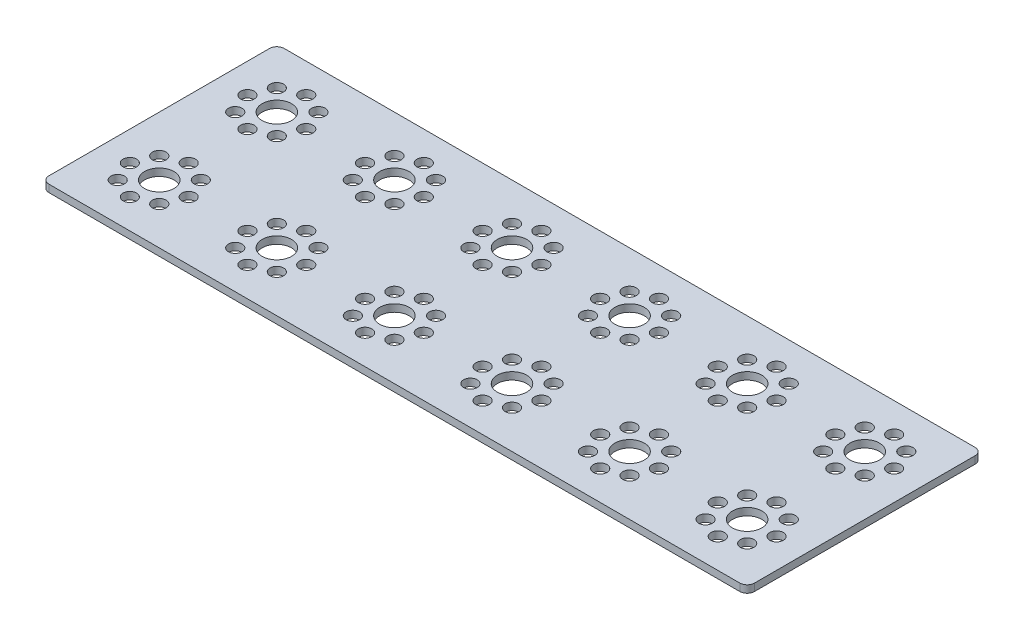
SolidWorks part; units mm, degrees
material "5052 Alloy"
ref_plane "Front Plane" through (0, 0, 0) normal (0, 0, 1) x (1, 0, 0)
ref_plane "Top Plane" through (0, 0, 0) normal (0, 1, 0) x (1, 0, 0)
ref_plane "Right Plane" through (0, 0, 0) normal (1, 0, 0) x (0, 0, -1)
sketch "Sketch1" plane through (0, 0, 0) normal (0, 1, 0) x (1, 0, 0)
  line L1 (0, 0) -> (192, 0)
  line L2 (0, 0) -> (0, 64)
  line L3 (0, 64) -> (192, 64)
  line L4 (192, 0) -> (192, 64)
  dimension "D1" = 192
  dimension "D2" = 64
extrude "Extrude1" add sketch "Sketch1" along normal blind 2
sketch "Sketch2" plane through (0, 2, 0) normal (0, 1, 0) x (1, 0, 0)
  line L0 (192, 64) -> (0, 64) construction
  line L1 (96, 64) -> (96, 84.1401) construction
  line L2 (96, 64) -> (96, -20.9972) construction
  line L3 (96, -20.9972) -> (96, 0) construction
  line L4 (0, 0) -> (192, 0) construction
  circle B0 centre (80, 48) radius 4
  circle B1 centre (80, 40) radius 1.85
  circle B2 centre (80, 56) radius 1.85
  circle B3 centre (72, 48) radius 1.85
  circle B4 centre (88, 48) radius 1.85
  circle B5 centre (85.66, 53.66) radius 1.85
  circle B6 centre (74.34, 53.66) radius 1.85
  circle B7 centre (85.66, 42.34) radius 1.85
  circle B8 centre (74.34, 42.34) radius 1.85
  circle B9 centre (48, 48) radius 4
  circle B10 centre (48, 40) radius 1.85
  circle B11 centre (48, 56) radius 1.85
  circle B12 centre (40, 48) radius 1.85
  circle B13 centre (56, 48) radius 1.85
  circle B14 centre (53.66, 53.66) radius 1.85
  circle B15 centre (42.34, 53.66) radius 1.85
  circle B16 centre (53.66, 42.34) radius 1.85
  circle B17 centre (42.34, 42.34) radius 1.85
  circle B18 centre (16, 48) radius 4
  circle B19 centre (16, 40) radius 1.85
  circle B20 centre (16, 56) radius 1.85
  circle B21 centre (8, 48) radius 1.85
  circle B22 centre (24, 48) radius 1.85
  circle B23 centre (21.66, 53.66) radius 1.85
  circle B24 centre (10.34, 53.66) radius 1.85
  circle B25 centre (21.66, 42.34) radius 1.85
  circle B26 centre (10.34, 42.34) radius 1.85
  circle B27 centre (112, 48) radius 4
  circle B28 centre (112, 40) radius 1.85
  circle B29 centre (112, 56) radius 1.85
  circle B30 centre (104, 48) radius 1.85
  circle B31 centre (120, 48) radius 1.85
  circle B32 centre (117.66, 53.66) radius 1.85
  circle B33 centre (106.34, 53.66) radius 1.85
  circle B34 centre (117.66, 42.34) radius 1.85
  circle B35 centre (106.34, 42.34) radius 1.85
  circle B36 centre (144, 48) radius 4
  circle B37 centre (144, 40) radius 1.85
  circle B38 centre (144, 56) radius 1.85
  circle B39 centre (136, 48) radius 1.85
  circle B40 centre (152, 48) radius 1.85
  circle B41 centre (149.66, 53.66) radius 1.85
  circle B42 centre (138.34, 53.66) radius 1.85
  circle B43 centre (149.66, 42.34) radius 1.85
  circle B44 centre (138.34, 42.34) radius 1.85
  circle B45 centre (176, 48) radius 4
  circle B46 centre (176, 40) radius 1.85
  circle B47 centre (176, 56) radius 1.85
  circle B48 centre (168, 48) radius 1.85
  circle B49 centre (184, 48) radius 1.85
  circle B50 centre (181.66, 53.66) radius 1.85
  circle B51 centre (170.34, 53.66) radius 1.85
  circle B52 centre (181.66, 42.34) radius 1.85
  circle B53 centre (170.34, 42.34) radius 1.85
  circle B54 centre (176, 16) radius 4
  circle B55 centre (176, 8) radius 1.85
  circle B56 centre (176, 24) radius 1.85
  circle B57 centre (168, 16) radius 1.85
  circle B58 centre (184, 16) radius 1.85
  circle B59 centre (181.66, 21.66) radius 1.85
  circle B60 centre (170.34, 21.66) radius 1.85
  circle B61 centre (181.66, 10.34) radius 1.85
  circle B62 centre (170.34, 10.34) radius 1.85
  circle B63 centre (144, 16) radius 4
  circle B64 centre (144, 8) radius 1.85
  circle B65 centre (144, 24) radius 1.85
  circle B66 centre (136, 16) radius 1.85
  circle B67 centre (152, 16) radius 1.85
  circle B68 centre (149.66, 21.66) radius 1.85
  circle B69 centre (138.34, 21.66) radius 1.85
  circle B70 centre (149.66, 10.34) radius 1.85
  circle B71 centre (138.34, 10.34) radius 1.85
  circle B72 centre (112, 16) radius 4
  circle B73 centre (112, 8) radius 1.85
  circle B74 centre (112, 24) radius 1.85
  circle B75 centre (104, 16) radius 1.85
  circle B76 centre (120, 16) radius 1.85
  circle B77 centre (117.66, 21.66) radius 1.85
  circle B78 centre (106.34, 21.66) radius 1.85
  circle B79 centre (117.66, 10.34) radius 1.85
  circle B80 centre (106.34, 10.34) radius 1.85
  circle B81 centre (80, 16) radius 4
  circle B82 centre (80, 8) radius 1.85
  circle B83 centre (80, 24) radius 1.85
  circle B84 centre (72, 16) radius 1.85
  circle B85 centre (88, 16) radius 1.85
  circle B86 centre (85.66, 21.66) radius 1.85
  circle B87 centre (74.34, 21.66) radius 1.85
  circle B88 centre (85.66, 10.34) radius 1.85
  circle B89 centre (74.34, 10.34) radius 1.85
  circle B90 centre (48, 16) radius 4
  circle B91 centre (48, 8) radius 1.85
  circle B92 centre (48, 24) radius 1.85
  circle B93 centre (40, 16) radius 1.85
  circle B94 centre (56, 16) radius 1.85
  circle B95 centre (53.66, 21.66) radius 1.85
  circle B96 centre (42.34, 21.66) radius 1.85
  circle B97 centre (53.66, 10.34) radius 1.85
  circle B98 centre (42.34, 10.34) radius 1.85
  circle B99 centre (16, 16) radius 4
  circle B100 centre (16, 8) radius 1.85
  circle B101 centre (16, 24) radius 1.85
  circle B102 centre (8, 16) radius 1.85
  circle B103 centre (24, 16) radius 1.85
  circle B104 centre (21.66, 21.66) radius 1.85
  circle B105 centre (10.34, 21.66) radius 1.85
  circle B106 centre (21.66, 10.34) radius 1.85
  circle B107 centre (10.34, 10.34) radius 1.85
  dimension "D1" = 16
  dimension "D2" = 16
  dimension "D3" = 32
  dimension "D4" = 32
  dimension "D5" = 16
  dimension "D6" = 32
  dimension "D7" = 32
  dimension "D8" = 32
sketch_block_instance "Block2-1"
sketch_block "Block2" parameters "D1"=8, "D4"=3.7, "D5"=3.7, "D7"=3.7, "D9"=3.7, "D10"=3.7, "D14"=3.7, "D16"=3.7, "D17"=3.7, "D2"=8, "D3"=8, "D6"=8, "D8"=8, "D11"=5.66, "D12"=5.66, "D13"=5.66, "D15"=5.66, "D18"=5.66, "D19"=5.66
sketch_block_instance "Block2-2"
sketch_block_instance "Block2-3"
sketch_block_instance "Block2-4"
sketch_block_instance "Block2-5"
sketch_block_instance "Block2-6"
sketch_block_instance "Block2-7"
sketch_block_instance "Block2-8"
sketch_block_instance "Block2-9"
sketch_block_instance "Block2-10"
sketch_block_instance "Block2-11"
sketch_block_instance "Block2-12"
extrude "Cut-Extrude1" cut sketch "Sketch2" against normal through all
fillet "Fillet1" radius 2 1 edges at (0, 1, 0)
fillet "Fillet2" radius 2 1 edges at (0, 1, -64)
fillet "Fillet3" radius 2 1 edges at (192, 1, 0)
fillet "Fillet4" radius 2 1 edges at (192, 1, -64)
